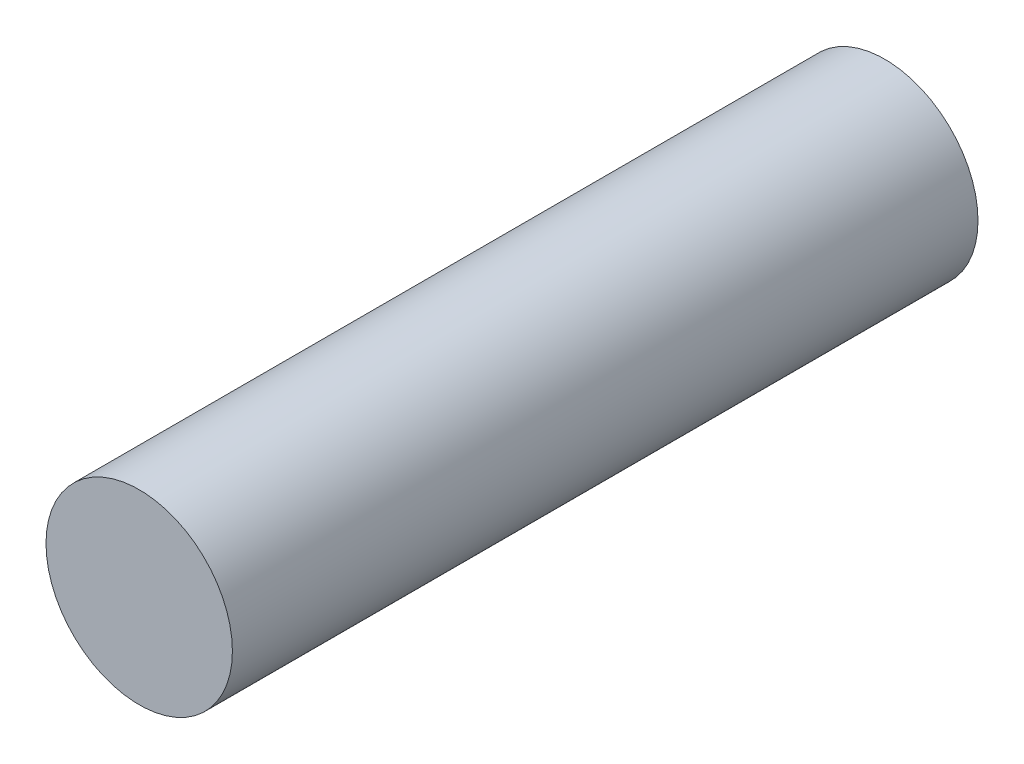
SolidWorks part; units mm, degrees
ref_plane "Front Plane" through (0, 0, 0) normal (0, 0, 1) x (1, 0, 0)
ref_plane "Top Plane" through (0, 0, 0) normal (0, 1, 0) x (1, 0, 0)
ref_plane "Right Plane" through (0, 0, 0) normal (1, 0, 0) x (0, 0, -1)
sketch "Sketch1" plane through (0, 0, 0) normal (0, 0, 1) x (1, 0, 0)
  circle A0 centre (0, 0) radius 3.175
  dimension "D1" = 6.35
extrude "Boss-Extrude1" add sketch "Sketch1" along normal blind 25.4
equation "\"Dout\"= .250in"
equation "\"D1@Sketch1\"=\"Dout\""
